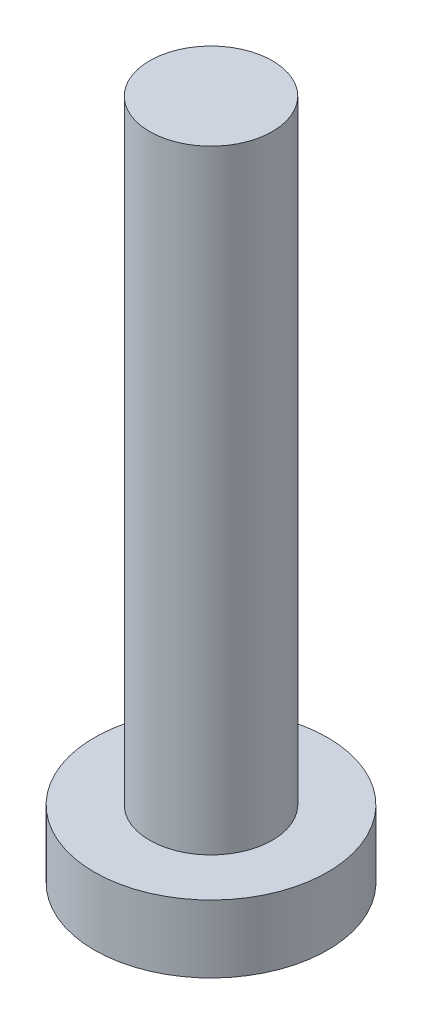
SolidWorks part; units mm, degrees
ref_plane "前视基准面" through (0, 0, 0) normal (0, 0, 1) x (1, 0, 0)
ref_plane "上视基准面" through (0, 0, 0) normal (0, 1, 0) x (1, 0, 0)
ref_plane "右视基准面" through (0, 0, 0) normal (1, 0, 0) x (0, 0, -1)
sketch "草图1" plane through (0, 0, 0) normal (0, 1, 0) x (1, 0, 0)
  circle A0 centre (0, 0) radius 3.8
  dimension "D1" = 7.6
extrude "凸台-拉伸1" add sketch "草图1" along normal blind 2.2
sketch "草图2" plane through (0, 2.2, 0) normal (0, 1, 0) x (1, 0, 0)
  circle A0 centre (0, 0) radius 2
  dimension "D1" = 4
extrude "凸台-拉伸2" add sketch "草图2" along normal blind 20
